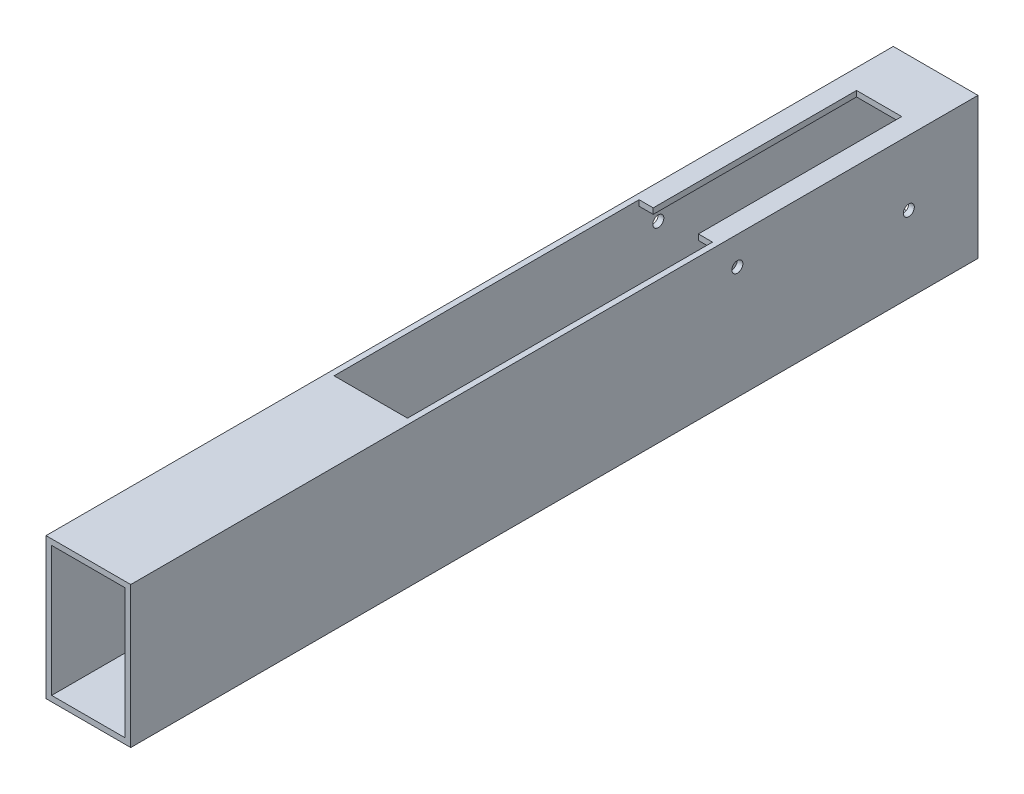
SolidWorks part; units mm, degrees
ref_plane "정면" through (0, 0, 0) normal (0, 0, 1) x (1, 0, 0)
ref_plane "윗면" through (0, 0, 0) normal (0, 1, 0) x (1, 0, 0)
ref_plane "우측면" through (0, 0, 0) normal (1, 0, 0) x (0, 0, -1)
sketch "스케치1" plane through (0, 0, 0) normal (0, 0, 1) x (1, 0, 0)
  line L0 (13, 23) -> (13, -23)
  line L1 (-15, 25) -> (15, 25)
  line L2 (-15, 25) -> (-15, -25)
  line L3 (-15, -25) -> (15, -25)
  line L4 (15, 25) -> (15, -25)
  line L5 (-15, 25) -> (15, -25) construction
  line L6 (-15, -25) -> (15, 25) construction
  line L7 (-13, -23) -> (13, -23)
  line L8 (-13, 23) -> (-13, -23)
  line L9 (-13, 23) -> (13, 23)
  point P0 (0, 0)
  dimension "D2" = 30
  dimension "D3" = 50
  dimension "D1" = 2
extrude "보스-돌출1" add sketch "스케치1" along normal blind 300
sketch "스케치3" plane through (0, 0, 0) normal (1, 0, 0) x (0, 0, -1)
  circle A0 centre (-85.2, 15) radius 1.95
  circle A1 centre (-24.5, 2) radius 1.95
  dimension "D1" = 3.9
  dimension "D2" = 3.9
extrude "컷-돌출2" cut sketch "스케치3" against normal through all both and the other way through all
sketch "스케치4" plane through (0, 0, 0) normal (1, 0, 0) x (0, 0, -1)
  line L0 (-20, 25) -> (-20, -23)
  line L1 (-48, -25) -> (-48, -23) construction
  line L2 (-300, -25) -> (0, -25) construction
  line L3 (-48, -25) -> (-74, -25) construction
  line L4 (-74, -25) -> (-74, -23) construction
  line L5 (-74, -23) -> (-97.25, -23)
  line L6 (-97.25, -23) -> (-97.25, 25)
  line L7 (-97.25, 25) -> (-20, 25)
  line L8 (-300, -23) -> (0, -23) construction
  line L9 (-48, -23) -> (-20, -23)
  line L10 (-74, -23) -> (-48, -23)
  dimension "D1" = 20
  dimension "D2" = 28
  dimension "D3" = 23.25
  dimension "D5" = 2
  dimension "D6" = 25
extrude "컷-돌출3" cut sketch "스케치4" against normal mid plane 16
sketch "스케치5" plane through (0, 0, 0) normal (1, 0, 0) x (0, 0, -1)
  line L0 (-59, -10.5) -> (-59, 23) construction
  line L2 (-59, 23) -> (-92, 23) construction
  line L3 (-92, 23) -> (-92, 25)
  line L4 (-92, 25) -> (-200, 25)
  line L5 (-200, 25) -> (-200, -25)
  line L6 (-200, -25) -> (-92, -25)
  line L7 (-72, -25) -> (-72, -10.5) construction
  line L8 (-72, -10.5) -> (-59, -10.5) construction
  line L9 (-300, 23) -> (0, 23) construction
  line L10 (-92, 23) -> (-92, -25)
  line L11 (-92, -25) -> (-72, -25) construction
  dimension "D1" = 33
  dimension "D2" = 25
  dimension "D3" = 13
  dimension "D4" = 10.5
  dimension "D5" = 128
  dimension "D6" = 25
  dimension "D7" = 59
extrude "컷-돌출4" cut sketch "스케치5" against normal mid plane 26
sketch "스케치6" plane through (0, 0, 0) normal (1, 0, 0) x (0, 0, -1)
  line L0 (-92, -23) -> (0, -23) construction
  line L1 (-65.476, -23) -> (-40.476, -23)
  line L2 (-65.476, -23) -> (-65.476, -25)
  line L3 (-65.476, -25) -> (-40.476, -25)
  line L4 (-40.476, -23) -> (-40.476, -25)
  line L5 (-300, -25) -> (0, -25) construction
  line L6 (-92, -23) -> (0, -23) construction
  line L7 (-89.1932, -23) -> (-78.3075, -23)
  line L8 (-89.1932, -23) -> (-89.1932, -25)
  line L9 (-89.1932, -25) -> (-78.3075, -25)
  line L10 (-78.3075, -23) -> (-78.3075, -25)
  dimension "D1" = 25
extrude "컷-돌출5" cut sketch "스케치6" against normal mid plane 10
sketch "스케치7" plane through (0, 0, 0) normal (1, 0, 0) x (0, 0, -1)
  line L0 (-92, -23) -> (0, -23) construction
  line L1 (0, -25) -> (-25, -25)
  line L2 (0, -25) -> (0, -23)
  line L3 (0, -23) -> (-25, -23)
  line L4 (-25, -25) -> (-25, -23)
  dimension "D1" = 25
extrude "컷-돌출6" cut sketch "스케치7" against normal mid plane 20
